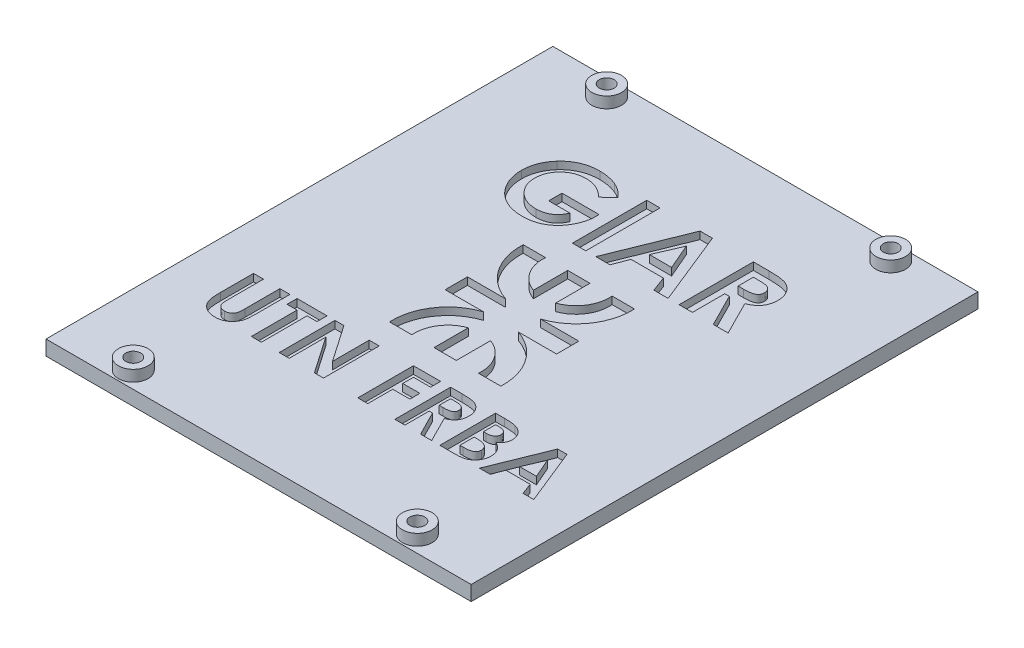
SolidWorks part; units mm, degrees
ref_plane "Front Plane" through (0, 0, 0) normal (0, 0, 1) x (1, 0, 0)
ref_plane "Top Plane" through (0, 0, 0) normal (0, 1, 0) x (1, 0, 0)
ref_plane "Right Plane" through (0, 0, 0) normal (1, 0, 0) x (0, 0, -1)
sketch "Sketch2" plane through (0, 0, 0) normal (0, 1, 0) x (1, 0, 0)
  line L0 (0, 0) -> (0, -50000) construction
  line L1 (-57.25, 68.25) -> (57.25, 68.25)
  line L2 (-57.25, 68.25) -> (-57.25, -68.25)
  line L3 (-57.25, -68.25) -> (57.25, -68.25)
  line L4 (57.25, 68.25) -> (57.25, -68.25)
  line L5 (-57.25, 68.25) -> (57.25, -68.25) construction
  line L6 (-57.25, -68.25) -> (57.25, 68.25) construction
  line L7 (0, 0) -> (50000, 0) construction
  circle A0 centre (-38.25, 63.75) radius 2
  circle A1 centre (-38.25, -63.75) radius 2
  circle A2 centre (38.25, -63.75) radius 2
  circle A3 centre (38.25, 63.75) radius 2
  point P0 (0, 0)
  dimension "D3" = 4
  dimension "D4" = 38.25
  dimension "D5" = 63.75
  dimension "D1" = 114.5
  dimension "D2" = 136.5
extrude "Boss-Extrude1" add sketch "Sketch2" along normal blind 4
sketch "Sketch3" plane through (0, 4, 0) normal (0, 1, 0) x (1, 0, 0)
  line L0 (-57.25, 25) -> (57.25, 25) construction
  line L1 (-9, 18) -> (-9, -18) construction
  line L2 (-15, 18) -> (15, 18) construction
  line L3 (-57.25, -45) -> (57.25, -45) construction
  line L4 (-47.25, 25) -> (57.25, 25) construction
  line L5 (-57.25, 68.25) -> (-57.25, -68.25) construction
  line L6 (57.25, -68.25) -> (57.25, 68.25) construction
  line L7 (-47.25, -45) -> (57.25, -45) construction
  line L8 (-57.25, -45) -> (-57.25, -68.25) construction
  line L9 (-57.25, -45) -> (-57.25, -25) construction
  line L10 (-57.25, -25) -> (-57.25, 25) construction
  line L11 (-57.25, 25) -> (-57.25, 45) construction
  line L12 (-57.25, 45) -> (-57.25, 68.25) construction
  line L13 (294.0315, 252.5659) -> (1544.0315, 252.5659) construction
  line L14 (-15, 18) -> (-15, -18) construction
  line L15 (-15, -18) -> (15, -18) construction
  line L16 (15, 18) -> (15, -18) construction
  line L17 (-15, 18) -> (15, -18) construction
  line L18 (-15, -18) -> (15, 18) construction
  line L19 (-3, 18) -> (-3, 8.7647) construction
  line L20 (3, 18) -> (3, 8.7647) construction
  line L21 (9, 18) -> (9, -18) construction
  line L22 (-15, 12) -> (15, 12) construction
  line L23 (-15, 6) -> (15, 6) construction
  line L24 (-15, 0) -> (15, 0) construction
  line L25 (-15, -6) -> (15, -6) construction
  line L26 (-15, -12) -> (15, -12) construction
  line L27 (-15, -3) -> (-4.6837, -3)
  line L28 (-15, 3) -> (-4.6837, 3)
  line L29 (-3, 18) -> (3, 18)
  line L30 (3, 18) -> (3, 8.7647)
  line L31 (3, -18) -> (-3, -18)
  line L32 (-3, -18) -> (-3, -8.7647)
  line L33 (-15, 3) -> (-15, -3)
  line L34 (15, 3) -> (15, -3)
  line L35 (0, -18) -> (0, -17.25) construction
  line L36 (-3, -8.7647) -> (-3, -18) construction
  line L37 (-3, 18) -> (-3, -18) construction
  line L38 (-4.6837, 3) -> (4.6837, 3) construction
  line L39 (3, -8.7647) -> (3, -18) construction
  line L40 (3, 18) -> (3, -18) construction
  line L41 (3, -8.7647) -> (3, -18)
  line L42 (4.6837, -3) -> (15, -3)
  line L43 (-15, -3) -> (15, -3) construction
  line L44 (-14.9812, -18) -> (-8.9687, -18)
  line L45 (8.9687, -18) -> (14.9812, -18)
  line L46 (0, 18) -> (0, 17.25)
  line L47 (-8.9687, 18) -> (-14.9812, 18)
  line L48 (-3, 8.7647) -> (-3, 18)
  line L49 (8.9687, 18) -> (14.9812, 18)
  line L52 (-15, 3) -> (15, 3) construction
  line L53 (4.6837, 3) -> (15, 3)
  arc A8 (14.9812, -18) -> (4.6837, -3) centre (0, -17.25) ccw
  arc A9 (8.9687, -18) -> (3, -8.7647) centre (0, -17.25) ccw
  arc A10 (-3, -8.7647) -> (-8.9687, -18) centre (0, -17.25) ccw
  arc A11 (-4.6837, -3) -> (-14.9812, -18) centre (0, -17.25) ccw
  arc A12 (-14.9812, 18) -> (-4.6837, 3) centre (0, 17.25) ccw
  arc A13 (-8.9687, 18) -> (-3, 8.7647) centre (0, 17.25) ccw
  arc A14 (3, 8.7647) -> (8.9687, 18) centre (0, 17.25) ccw
  arc A15 (4.6837, 3) -> (14.9812, 18) centre (0, 17.25) ccw
  text T0 "GIAR" font "Century Gothic" height 20
  text T1 "UTN FRBA" font "Century Gothic" height 20
  dimension "D3" = 50
  dimension "D6" = 6
  dimension "D15" = 3
  dimension "D17" = 0.75
  dimension "D18" = 0.75
  dimension "D1" = 20
  dimension "D2" = 20
  dimension "D4" = 36
  dimension "D5" = 30
  dimension "D7" = 6
  dimension "D8" = 6
  dimension "D9" = 6
  dimension "D10" = 6
  dimension "D11" = 6
  dimension "D12" = 6
  dimension "D13" = 6
  dimension "D14" = 6
  dimension "D16" = 3
extrude "Cut-Extrude1" cut sketch "Sketch3" against normal blind 2
sketch "Sketch4" plane through (0, 4, 4) normal (0, 1, 0) x (1, 0, 0)
  line L0 (-57.25, 29) -> (57.25, 29) construction
  line L3 (-57.25, -36) -> (57.25, -36) construction
  line L4 (-47.25, 29) -> (57.25, 29) construction
  line L5 (-8.9687, 22) -> (-14.9812, 22) construction
  line L6 (-14.9812, -14) -> (-8.9687, -14) construction
  line L7 (-47.25, -36) -> (57.25, -36) construction
  line L8 (-57.25, 72.25) -> (-57.25, -64.25) construction
  line L9 (-57.25, -36) -> (-57.25, -21) construction
  line L10 (-57.25, -21) -> (-57.25, 29) construction
  line L11 (-57.25, 29) -> (-57.25, 49) construction
  line L13 (294.0315, 252.5659) -> (1544.0315, 252.5659) construction
  line L17 (57.25, -64.25) -> (57.25, 72.25) construction
  text T0 "GIAR" font "Century Gothic" height 20
  text T1 "UTN FRBA" font "Century Gothic" height 15
  dimension "D3" = 7
  dimension "D1" = 15
  dimension "D2" = 20
  dimension "D4" = 7
extrude "Cut-Extrude2" cut sketch "Sketch4" against normal blind 2
sketch "Sketch5" plane through (0, 4, 0) normal (0, 1, 0) x (1, 0, 0)
  circle A0 centre (38.25, -63.75) radius 2 construction
  circle A1 centre (-38.25, -63.75) radius 2 construction
  circle A2 centre (38.25, 63.75) radius 2 construction
  circle A3 centre (-38.25, 63.75) radius 2 construction
  circle A12 centre (38.25, -63.75) radius 2
  circle A13 centre (-38.25, -63.75) radius 2
  circle A14 centre (38.25, 63.75) radius 2
  circle A15 centre (-38.25, 63.75) radius 2
  circle A16 centre (38.25, -63.75) radius 4
  circle A17 centre (-38.25, -63.75) radius 4
  circle A18 centre (38.25, 63.75) radius 4
  circle A19 centre (-38.25, 63.75) radius 4
  dimension "D1" = 2
extrude "Boss-Extrude2" add sketch "Sketch5" along normal blind 3
